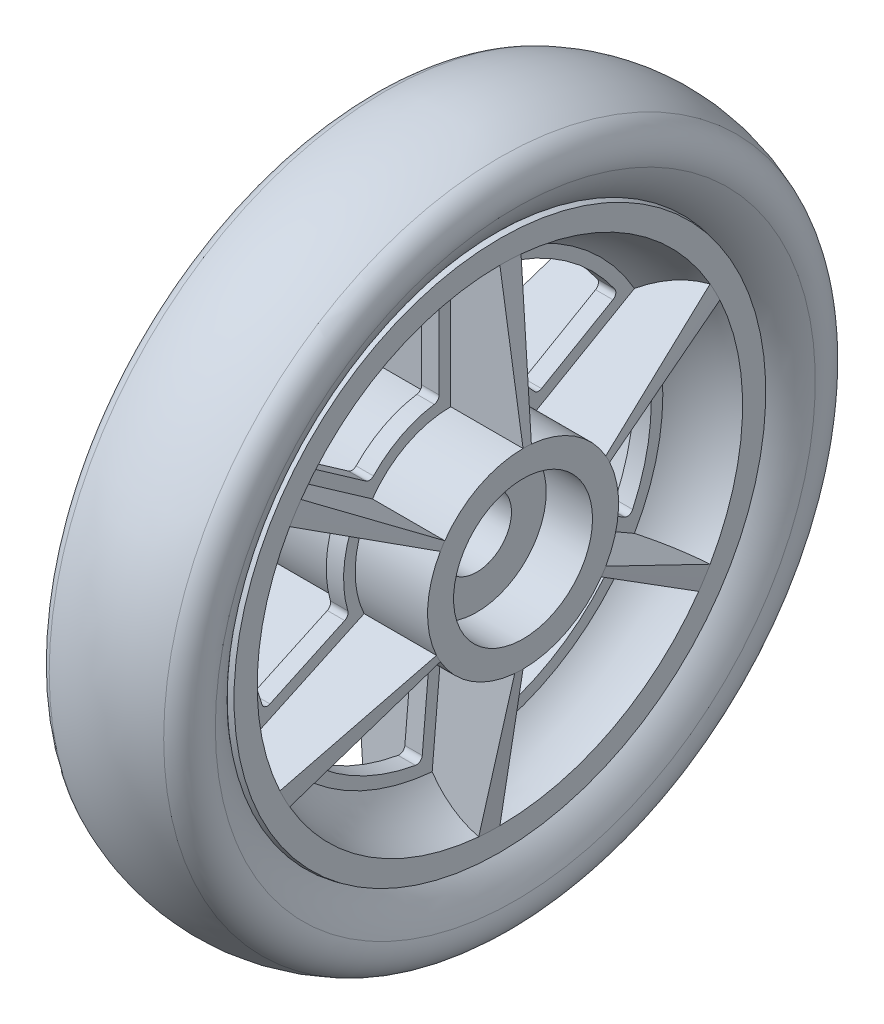
SolidWorks part; units mm, degrees
ref_plane "Plano frontal" through (0, 0, 0) normal (0, 0, 1) x (1, 0, 0)
ref_plane "Plano superior" through (0, 0, 0) normal (0, 1, 0) x (1, 0, 0)
ref_plane "Plano direito" through (0, 0, 0) normal (1, 0, 0) x (0, 0, -1)
sketch "Esboço1" plane through (0, 0, 0) normal (0, 0, 1) x (1, 0, 0)
  line L0 (0, 0) -> (0, 95.3733) construction
  line L1 (10, 41.9239) -> (10, 45.9239)
  line L2 (10, 45.9239) -> (10, 41.9239)
  line L3 (-10, 45.9239) -> (-10, 41.9239)
  line L4 (10, 0) -> (10, 95.3733) construction
  line L5 (0, 0) -> (14.9869, 0) construction
  line L6 (9, 46.1303) -> (9, 42.7076)
  line L7 (-9, 46.1303) -> (-9, 42.7076)
  line L10 (-9, 46.1303) -> (-9, 43.5347) construction
  line L14 (-8.6354, 42.6036) -> (-8.6354, 42.6036) construction
  line L15 (-8.6354, 42.6036) -> (-8.6354, 42.6036) construction
  arc A1 (10, 45.9239) -> (9, 46.1303) centre (0, 0) ccw
  arc A2 (1, 35.9861) -> (-1, 35.9861) centre (0, 0) ccw
  arc A3 (-10, 41.9239) -> (-1, 35.9861) centre (-13.2085, 27.271) cw
  arc A4 (10, 41.9239) -> (1, 35.9861) centre (13.2085, 27.271) ccw
  arc A5 (-9, 46.1303) -> (-10, 45.9239) centre (0, 0) ccw
  arc A6 (9, 42.7076) -> (0.5036, 36.9966) centre (13.2085, 27.271) ccw
  arc A7 (0.5036, 36.9966) -> (-0.5036, 36.9966) centre (0, 0) ccw
  arc A8 (-9, 42.7076) -> (-0.5036, 36.9966) centre (-13.2085, 27.271) cw
  arc A10 (9.7861, 42.9007) -> (0.5036, 36.9966) centre (13.2085, 27.271) ccw construction
  arc A11 (-8.6354, 42.6036) -> (-0.5036, 36.9966) centre (-13.2085, 27.271) cw construction
  arc A18 (-8.6354, 42.6036) -> (-8.6354, 42.6036) centre (-8.6354, 42.6036) cw construction
  dimension "D1" = 36
  dimension "D2" = 47
  dimension "D6" = 9
  dimension "D7" = 15
  dimension "D5" = 10
  dimension "D4" = 4
  dimension "D3" = 1
  dimension "D8" = 1
  dimension "D9" = 1
revolve "Revolução2" add sketch "Esboço1" angle 360 about L5
sketch "Esboço2" plane through (0, 0, 0) normal (0, 0, 1) x (1, 0, 0)
  line L0 (0, 0) -> (0, 95.3733) construction
  line L4 (0, 0) -> (0, 71.3665) construction
  arc A1 (-12.6635, 51.8176) -> (12.6635, 51.8176) centre (0, 55.9513) ccw
  arc A2 (9.888, 57.9615) -> (12.6635, 51.8176) centre (7.9104, 53.3692) cw
  arc A5 (9.888, 57.9615) -> (-9.888, 57.9615) centre (0, 35) ccw
  arc A6 (-9.888, 57.9615) -> (-12.6635, 51.8176) centre (-7.9104, 53.3692) ccw
  dimension "D1" = 10
  dimension "D2" = 13.3211
  dimension "D3" = 7.9104
  dimension "D4" = 50
revolve "Revolução3" add sketch "Esboço2" angle 360 about L5
sketch "Esboço5" plane through (0, 0, 0) normal (0, 1, 0) x (1, 0, 0)
  line L0 (0, 0) -> (-36.5743, 0) construction
  line L1 (0, 0) -> (0, 25.5384) construction
  line L2 (-1.5, 40) -> (1.5, 40)
  line L3 (-1.5, 40) -> (-1.5, 16.5)
  line L4 (-1.5, 16.5) -> (-14, 16.5)
  line L5 (-14, 16.5) -> (-14, 12)
  line L6 (-14, 12) -> (-6, 12)
  line L7 (-6, 12) -> (-6, 6)
  line L8 (-6, 6) -> (6, 6)
  line L9 (6, 12) -> (6, 6)
  line L10 (14, 12) -> (6, 12)
  line L11 (14, 16.5) -> (14, 12)
  line L12 (1.5, 16.5) -> (14, 16.5)
  line L13 (1.5, 40) -> (1.5, 16.5)
  point P13 (0, 6)
  point P18 (0, 40)
  dimension "D1" = 1.5
  dimension "D2" = 40
  dimension "D3" = 16.5
  dimension "D4" = 14
  dimension "D5" = 12
  dimension "D6" = 8
  dimension "D7" = 6
revolve "Revolução4" add sketch "Esboço5" angle 360 about L0
sketch "Esboço7" plane through (0, 0, 0) normal (0, 0, 1) x (1, 0, 0)
  line L0 (-14, 16.5) -> (-10, 41.9239)
  line L1 (-10, 41.9239) -> (10, 41.9239)
  line L2 (10, 41.9239) -> (14, 16.5)
  line L3 (14, 16.5) -> (-14, 16.5)
  line L4 (0, 0) -> (-21.4069, 0) construction
revolve "Revolução5" add sketch "Esboço7" angle 5 about L4
pattern_circular "PadrãoCircular1" count 6 over 360 about axis through (14, 0, 0) along (1, 0, 0) of "Revolução5"
sketch "Esboço9" plane through (-1.5, 0, 0) normal (-1, 0, 0) x (0, 0, 1)
  line L2 (2, 18.3916) -> (2, 34.5893)
  line L3 (13.9183, 12.1873) -> (27.1868, 21.4779)
  line L4 (0, 36.6471) -> (0, 16.5) construction
  line L5 (13.516, 9.464) -> (30.0196, 21.0199) construction
  arc A2 (27.1868, 21.4779) -> (2, 34.5893) centre (0, 0) ccw
  arc A3 (13.9183, 12.1873) -> (2, 18.3916) centre (0, 0) ccw
  arc A4 (13.516, 9.464) -> (0, 16.5) centre (0, 0) ccw construction
  arc A5 (30.0196, 21.0199) -> (0, 36.6471) centre (0, 0) ccw construction
  dimension "D1" = 34.6471
  dimension "D2" = 18.5
  dimension "D5" = 2
  dimension "D6" = 2
  dimension "D3" = 2
  dimension "D4" = 2
extrude "Corte-extrusão2" cut sketch "Esboço9" against normal mid plane 23
fillet "Filete1" radius 1 4 edges at (0, 18.3916, 2) (0, 12.1873, 13.9183) (0, 34.5893, 2) (0, 21.4779, 27.1868)
pattern_circular "PadrãoCircular2" count 6 over 360 about axis through (0, 0, 0) along (1, 0, 0) of "Filete1", "Corte-extrusão2"
